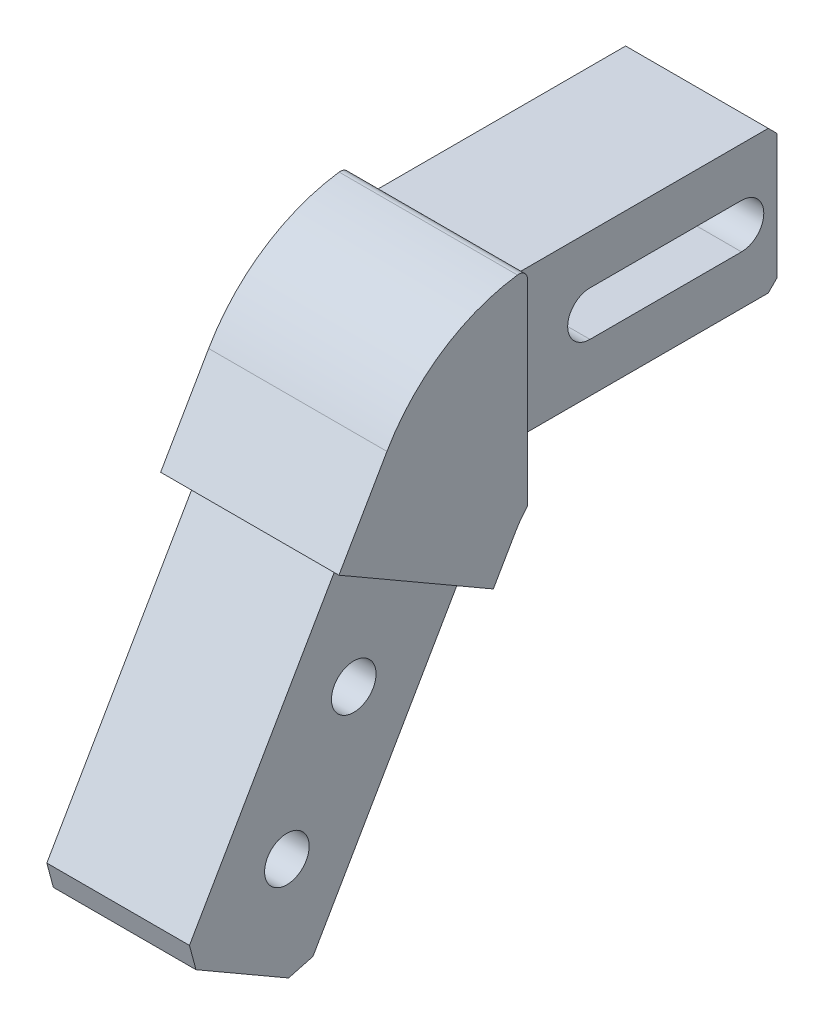
SolidWorks part; units mm, degrees
material "PA Type 6"
ref_plane "Front Plane" through (0, 0, 0) normal (0, 0, 1) x (1, 0, 0)
ref_plane "Top Plane" through (0, 0, 0) normal (0, 1, 0) x (1, 0, 0)
ref_plane "Right Plane" through (0, 0, 0) normal (1, 0, 0) x (0, 0, -1)
sketch "Sketch1" plane through (0, 0, 0) normal (1, 0, 0) x (0, 0, -1)
  line L7 (0, 0) -> (54.8406, 0) construction
  line L8 (0, 0) -> (-20, -34.641) construction
  line L10 (40, 3) -> (40, 17)
  line L12 (-5.7735, 10) -> (-11.1603, 0.6699)
  line L13 (8.6603, -5) -> (6.1603, -9.3301)
  line L14 (-8.6603, 5) -> (-28.6603, -29.641) construction
  line L15 (8.6603, -5) -> (-11.3397, -39.641) construction
  line L16 (0, 0) -> (19.0643, -11.0068) construction
  line L17 (-26.9282, -30.641) -> (-13.0718, -38.641)
  line L18 (40, 10) -> (-19.6071, 10) construction
  line L19 (0, 0) -> (0, 39.1739) construction
  line L20 (19, 12.5) -> (36, 12.5)
  line L21 (36, 7.5) -> (19, 7.5)
  line L22 (40, 36.5213) -> (40, -25.9808) construction
  line L24 (-17.2892, 18) -> (55.6207, 18) construction
  line L25 (-17.2892, 2) -> (55.6207, 2) construction
  line L26 (15, 18) -> (39, 18)
  line L27 (15, 2) -> (39, 2)
  line L30 (39, 18) -> (40, 17)
  line L31 (39, 2) -> (40, 3)
  line L32 (-11.1603, 0.6699) -> (-9.4282, -0.3301)
  line L33 (-26.9282, -30.641) -> (-9.4282, -0.3301)
  line L34 (-13.0718, -38.641) -> (4.4282, -8.3301)
  line L35 (4.4282, -8.3301) -> (6.1603, -9.3301)
  line L36 (-28.6603, -29.641) -> (-11.3397, -39.641) construction
  line L37 (10, 24.8019) -> (10, -11.0068) construction
  line L38 (-11.1603, 0.6699) -> (6.1603, -9.3301) construction
  line L39 (15, 18) -> (10, 18)
  line L40 (10, 18) -> (10, 19.9401)
  line L41 (15, 2) -> (10, 2)
  line L42 (10, 2) -> (10, -3.1875)
  arc A0 (8.6603, -5) -> (10, -3.1875) centre (17.3205, -10) cw
  arc A1 (-5.7735, 10) -> (10, 19.9401) centre (11.547, 0) cw
  arc A2 (36, 7.5) -> (36, 12.5) centre (36, 10) ccw
  arc A3 (19, 12.5) -> (19, 7.5) centre (19, 10) ccw
  circle A4 centre (-15, -25.9808) radius 2.5
  circle A5 centre (-7.5, -12.9904) radius 2.5
  point P14 (11.547, 0)
  point P19 (0, 20)
  point P26 (15, 36.5213)
  point P35 (15, -25.9808)
  point P41 (40, 18)
  point P43 (40, 2)
  dimension "D7" = 10
  dimension "D8" = 20
  dimension "D9" = 5
  dimension "D10" = 5
  dimension "D13" = 5
  dimension "D14" = 5
  dimension "D1" = 120
  dimension "D2" = 10
  dimension "D4" = 40
  dimension "D5" = 40
  dimension "D6" = 35
  dimension "D11" = 4
  dimension "D12" = 17
  dimension "D15" = 10
  dimension "D16" = 15
  dimension "D19" = 2
  dimension "D3" = 10
extrude "Boss-Extrude1" add sketch "Sketch1" along normal blind 16
sketch "Sketch2" plane through (16, 0, 0) normal (1, 0, 0) x (0, 0, -1)
  line L1 (-11.1603, 0.6699) -> (6.1603, -9.3301)
  line L2 (-11.1603, 0.6699) -> (-5.7735, 10)
  line L3 (6.1603, -9.3301) -> (8.6603, -5)
  line L5 (10, 19.9401) -> (10, -3.1875)
  arc A1 (8.6603, -5) -> (10, -3.1875) centre (17.3205, -10) cw
  arc A2 (-5.7735, 10) -> (10, 19.9401) centre (11.547, 0) cw
extrude "Boss-Extrude2" add sketch "Sketch2" along normal blind 2 and the other way blind 18
chamfer "Chamfer1" distance 2 angle 45 2 edges at (8, -38.641, 13.0718) (8, -30.641, 26.9282)
fillet "Fillet1" radius 1 1 edges at (8, 19.9401, -10)
